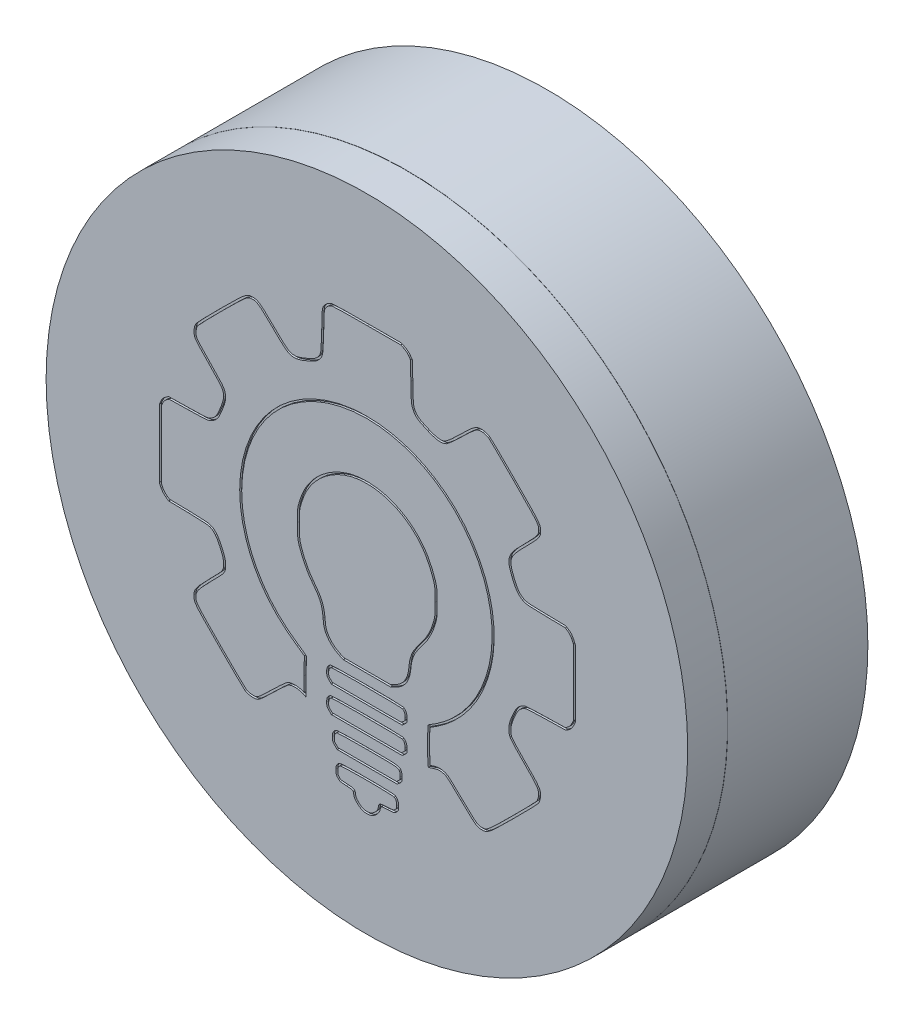
SolidWorks part; units mm, degrees
ref_plane "Front Plane" through (0, 0, 0) normal (0, 0, 1) x (1, 0, 0)
ref_plane "Top Plane" through (0, 0, 0) normal (0, 1, 0) x (1, 0, 0)
ref_plane "Right Plane" through (0, 0, 0) normal (1, 0, 0) x (0, 0, -1)
sketch "Sketch1" plane through (0, 0, 0) normal (0, 0, 1) x (1, 0, 0)
  circle A0 centre (0, 0) radius 15.025
  circle A1 centre (0, 0) radius 16.025
  dimension "D1" = 30.05
  dimension "D2" = 1
extrude "Boss-Extrude1" add sketch "Sketch1" along normal blind 7
sketch "Sketch2" plane through (0, 0, 7) normal (0, 0, 1) x (1, 0, 0)
  circle A0 centre (0, 0) radius 16.025
  circle A1 centre (0, 0) radius 16.025 construction
  point P8 (0, 0)
extrude "Boss-Extrude3" add sketch "Sketch2" along normal blind 2
sketch "Sketch4" plane through (0, 0, 9) normal (0, 0, 1) x (1, 0, 0)
  line L0 (-8.9288, 2.3101) -> (-9.9025, 2.2925)
  line L1 (-9.9025, 2.2925) -> (-10.0506, 2.1937)
  line L2 (-10.287, 1.9115) -> (-10.3717, 1.7281)
  line L3 (-10.3717, 1.7281) -> (-10.3717, 0.0312)
  line L4 (-10.3717, 0.0312) -> (-10.3717, -1.6621)
  line L5 (-10.3717, -1.6621) -> (-10.2835, -1.8421)
  line L6 (-10.0471, -2.1208) -> (-9.9025, -2.2231)
  line L7 (-9.9025, -2.2231) -> (-8.9288, -2.2407)
  line L8 (-3.1997, -7.2043) -> (-3.0339, -7.2819)
  line L9 (-3.0339, -7.2819) -> (-3.0339, -6.3999)
  line L10 (8.9641, -2.2442) -> (9.9378, -2.2231)
  line L11 (9.9378, -2.2231) -> (10.0789, -2.1278)
  line L12 (10.3152, -1.8491) -> (10.407, -1.6621)
  line L13 (10.407, -1.6621) -> (10.407, 0.0312)
  line L14 (10.407, 0.0312) -> (10.407, 1.7281)
  line L15 (10.407, 1.7281) -> (10.3223, 1.9115)
  line L16 (10.0859, 2.1937) -> (9.9378, 2.2925)
  line L17 (9.9378, 2.2925) -> (8.9641, 2.3101)
  line L18 (2.2931, 8.9988) -> (2.2754, 9.9548)
  line L19 (2.2754, 9.9548) -> (2.1802, 10.096)
  line L20 (1.9015, 10.3323) -> (1.7145, 10.424)
  line L21 (1.7145, 10.424) -> (0.0212, 10.4205)
  line L22 (-1.4182, -4.6149) -> (-1.1818, -4.7278)
  line L23 (-1.1818, -4.7278) -> (0, -4.7278)
  line L24 (0, -4.7278) -> (1.1818, -4.7278)
  line L25 (1.1818, -4.7278) -> (1.4182, -4.6149)
  line L26 (-1.8909, -5.966) -> (-1.7709, -6.086)
  line L27 (-1.7709, -6.086) -> (-0.0035, -6.086)
  line L28 (-0.0035, -6.086) -> (1.7604, -6.086)
  line L29 (1.7604, -6.086) -> (1.8874, -5.9766)
  line L30 (-1.8909, -7.2815) -> (-1.7709, -7.4014)
  line L31 (-1.7709, -7.4014) -> (-0.0035, -7.4014)
  line L32 (-0.0035, -7.4014) -> (1.7604, -7.4014)
  line L33 (1.7604, -7.4014) -> (1.8874, -7.292)
  line L34 (-1.6087, -8.6471) -> (-1.4887, -8.7671)
  line L35 (-1.4887, -8.7671) -> (0.0141, -8.7671)
  line L36 (0.0141, -8.7671) -> (1.5134, -8.7671)
  line L37 (1.5134, -8.7671) -> (1.6404, -8.6577)
  line L76 (-8.927, 2.2102) -> (-9.8714, 2.193)
  line L77 (-9.8714, 2.193) -> (-9.9945, 2.111)
  line L78 (-10.1966, 1.8688) -> (-10.2717, 1.7061)
  line L79 (-10.2717, 1.7061) -> (-10.2717, 0.0312)
  line L80 (-10.2717, 0.0312) -> (-10.2717, -1.6389)
  line L81 (-10.2717, -1.6389) -> (-10.194, -1.7973)
  line L82 (-9.9909, -2.0381) -> (-9.8699, -2.1236)
  line L83 (-9.8699, -2.1236) -> (-8.927, -2.1407)
  line L84 (-3.1583, -7.1133) -> (-3.1339, -7.1247)
  line L85 (-3.1339, -7.1247) -> (-3.1339, -6.3999)
  line L86 (8.9619, -2.1442) -> (9.9062, -2.1237)
  line L87 (9.9062, -2.1237) -> (10.0235, -2.0445)
  line L88 (10.2258, -1.8044) -> (10.307, -1.6389)
  line L89 (10.307, -1.6389) -> (10.307, 0.0312)
  line L90 (10.307, 0.0312) -> (10.307, 1.7061)
  line L91 (10.307, 1.7061) -> (10.2319, 1.8688)
  line L92 (10.0298, 2.111) -> (9.9067, 2.193)
  line L93 (9.9067, 2.193) -> (8.9622, 2.2102)
  line L94 (2.1931, 8.997) -> (2.176, 9.9234)
  line L95 (2.176, 9.9234) -> (2.0969, 10.0406)
  line L96 (1.8568, 10.2429) -> (1.6914, 10.324)
  line L97 (1.6914, 10.324) -> (0.0212, 10.3205)
  line L98 (-1.3752, -4.5246) -> (-1.1592, -4.6278)
  line L99 (-1.1592, -4.6278) -> (0, -4.6278)
  line L100 (0, -4.6278) -> (1.1592, -4.6278)
  line L101 (1.1592, -4.6278) -> (1.3753, -4.5245)
  line L102 (-1.8202, -5.8953) -> (-1.7295, -5.986)
  line L103 (-1.7295, -5.986) -> (-0.0035, -5.986)
  line L104 (-0.0035, -5.986) -> (1.7232, -5.986)
  line L105 (1.7232, -5.986) -> (1.8212, -5.9016)
  line L106 (-1.8202, -7.2108) -> (-1.7295, -7.3014)
  line L107 (-1.7295, -7.3014) -> (-0.0035, -7.3014)
  line L108 (-0.0035, -7.3014) -> (1.7232, -7.3014)
  line L109 (1.7232, -7.3014) -> (1.8212, -7.2171)
  line L110 (-1.538, -8.5764) -> (-1.4473, -8.6671)
  line L111 (-1.4473, -8.6671) -> (0.0141, -8.6671)
  line L112 (0.0141, -8.6671) -> (1.4763, -8.6671)
  line L113 (1.4763, -8.6671) -> (1.5743, -8.5827)
  spline S0 degree 3 poles (-1.7815, 10.3817) (-1.9438, 10.3217) (-2.0673, 10.223) (-2.159, 10.0783) knots 0 0 0 0 1 1 1 1
  spline S1 degree 3 poles (-2.159, 10.0783) (-2.2366, 9.9513) (-2.2401, 9.9125) (-2.2578, 8.9953) knots 0 0 0 0 1 1 1 1
  spline S2 degree 3 poles (-2.2578, 8.9953) (-2.2789, 7.944) (-2.2895, 7.8911) (-2.5118, 7.6688) knots 0 0 0 0 1 1 1 1
  spline S3 degree 3 poles (-2.5118, 7.6688) (-2.6564, 7.5207) (-3.2879, 7.249) (-3.5384, 7.2208) knots 0 0 0 0 1 1 1 1
  spline S4 degree 3 poles (-3.5384, 7.2208) (-3.8488, 7.1891) (-3.9582, 7.2631) (-4.6426, 7.944) knots 0 0 0 0 1 1 1 1
  spline S5 degree 3 poles (-4.6426, 7.944) (-5.2811, 8.579) (-5.4398, 8.6919) (-5.6797, 8.6954) knots 0 0 0 0 1 1 1 1
  spline S6 degree 3 poles (-5.6797, 8.6954) (-6.0043, 8.6954) (-6.0149, 8.6884) (-7.2778, 7.4325) knots 0 0 0 0 1 1 1 1
  spline S7 degree 3 poles (-7.2778, 7.4325) (-7.934, 6.7763) (-8.5019, 6.1942) (-8.5408, 6.1307) knots 0 0 0 0 1 1 1 1
  spline S8 degree 3 poles (-8.5408, 6.1307) (-8.6325, 5.9826) (-8.6642, 5.7074) (-8.6078, 5.5345) knots 0 0 0 0 1 1 1 1
  spline S9 degree 3 poles (-8.6078, 5.5345) (-8.5725, 5.4322) (-8.3926, 5.2241) (-7.8987, 4.7231) knots 0 0 0 0 1 1 1 1
  spline S10 degree 3 poles (-7.8987, 4.7231) (-7.1967, 4.0105) (-7.1614, 3.9576) (-7.1614, 3.626) knots 0 0 0 0 1 1 1 1
  spline S11 degree 3 poles (-7.1614, 3.626) (-7.1614, 3.4355) (-7.4189, 2.7829) (-7.5565, 2.61) knots 0 0 0 0 1 1 1 1
  spline S12 degree 3 poles (-7.5565, 2.61) (-7.6165, 2.543) (-7.7294, 2.4477) (-7.807, 2.4054) knots 0 0 0 0 1 1 1 1
  spline S13 degree 3 poles (-7.807, 2.4054) (-7.9481, 2.3348) (-8.0116, 2.3278) (-8.9288, 2.3101) knots 0 0 0 0 1 1 1 1
  spline S14 degree 3 poles (-10.0506, 2.1937) (-10.153, 2.1232) (-10.227, 2.0385) (-10.287, 1.9115) knots 0 0 0 0 1 1 1 1
  spline S15 degree 3 poles (-10.2835, -1.8421) (-10.227, -1.9549) (-10.1388, -2.0608) (-10.0471, -2.1208) knots 0 0 0 0 1 1 1 1
  spline S16 degree 3 poles (-8.9288, -2.2407) (-7.8281, -2.2619) (-7.7929, -2.2689) (-7.5706, -2.5264) knots 0 0 0 0 1 1 1 1
  spline S17 degree 3 poles (-7.5706, -2.5264) (-7.4295, -2.6923) (-7.2108, -3.172) (-7.1649, -3.4296) knots 0 0 0 0 1 1 1 1
  spline S18 degree 3 poles (-7.1649, -3.4296) (-7.1473, -3.5178) (-7.1508, -3.6518) (-7.1684, -3.7506) knots 0 0 0 0 1 1 1 1
  spline S19 degree 3 poles (-7.1684, -3.7506) (-7.2037, -3.9023) (-7.2566, -3.9693) (-7.8528, -4.569) knots 0 0 0 0 1 1 1 1
  spline S20 degree 3 poles (-7.8528, -4.569) (-8.5196, -5.2428) (-8.6395, -5.4122) (-8.6431, -5.6591) knots 0 0 0 0 1 1 1 1
  spline S21 degree 3 poles (-8.6431, -5.6591) (-8.6431, -5.9801) (-8.6289, -5.9978) (-7.3766, -7.2607) knots 0 0 0 0 1 1 1 1
  spline S22 degree 3 poles (-7.3766, -7.2607) (-6.7239, -7.9169) (-6.1419, -8.4849) (-6.0784, -8.5237) knots 0 0 0 0 1 1 1 1
  spline S23 degree 3 poles (-6.0784, -8.5237) (-5.9302, -8.6154) (-5.655, -8.6471) (-5.4822, -8.5907) knots 0 0 0 0 1 1 1 1
  spline S24 degree 3 poles (-5.4822, -8.5907) (-5.3799, -8.5589) (-5.1788, -8.3826) (-4.6919, -7.9028) knots 0 0 0 0 1 1 1 1
  spline S25 degree 3 poles (-4.6919, -7.9028) (-4.3321, -7.55) (-3.9829, -7.229) (-3.9158, -7.1937) knots 0 0 0 0 1 1 1 1
  spline S26 degree 3 poles (-3.9158, -7.1937) (-3.743, -7.102) (-3.4149, -7.109) (-3.1997, -7.2043) knots 0 0 0 0 1 1 1 1
  spline S27 degree 3 poles (-3.0339, -6.3999) (-3.0339, -5.9166) (-3.0304, -5.5109) (-3.0268, -5.4933) knots 0 0 0 0 1 1 1 1
  spline S28 degree 3 poles (-3.0268, -5.4933) (-3.0268, -5.4792) (-3.2068, -5.3451) (-3.4325, -5.1934) knots 0 0 0 0 1 1 1 1
  spline S29 degree 3 poles (-3.4325, -5.1934) (-4.6567, -4.375) (-5.4892, -3.2884) (-5.9408, -1.9197) knots 0 0 0 0 1 1 1 1
  spline S30 degree 3 poles (-5.9408, -1.9197) (-6.7804, 0.6098) (-5.8984, 3.432) (-3.7712, 5.0336) knots 0 0 0 0 1 1 1 1
  spline S31 degree 3 poles (-3.7712, 5.0336) (-1.6898, 6.5964) (1.1183, 6.7163) (3.3338, 5.3334) knots 0 0 0 0 1 1 1 1
  spline S32 degree 3 poles (3.3338, 5.3334) (5.7503, 3.8271) (6.8404, 0.8108) (5.9443, -1.9056) knots 0 0 0 0 1 1 1 1
  spline S33 degree 3 poles (5.9443, -1.9056) (5.5033, -3.2532) (4.6496, -4.3785) (3.4713, -5.1688) knots 0 0 0 0 1 1 1 1
  spline S34 degree 3 poles (3.4713, -5.1688) (3.2738, -5.2993) (3.0974, -5.4122) (3.0727, -5.4192) knots 0 0 0 0 1 1 1 1
  spline S35 degree 3 poles (3.0727, -5.4192) (3.0092, -5.4404) (3.0127, -7.2713) (3.0762, -7.2607) knots 0 0 0 0 1 1 1 1
  spline S36 degree 3 poles (3.0762, -7.2607) (3.1009, -7.2572) (3.2173, -7.2184) (3.3338, -7.1796) knots 0 0 0 0 1 1 1 1
  spline S37 degree 3 poles (3.3338, -7.1796) (3.5631, -7.0949) (3.7712, -7.1055) (3.9688, -7.2043) knots 0 0 0 0 1 1 1 1
  spline S38 degree 3 poles (3.9688, -7.2043) (4.0252, -7.236) (4.3603, -7.5429) (4.7096, -7.8887) knots 0 0 0 0 1 1 1 1
  spline S39 degree 3 poles (4.7096, -7.8887) (5.3516, -8.5237) (5.4928, -8.626) (5.7185, -8.626) knots 0 0 0 0 1 1 1 1
  spline S40 degree 3 poles (5.7185, -8.626) (6.0325, -8.626) (6.0572, -8.6083) (7.3131, -7.3595) knots 0 0 0 0 1 1 1 1
  spline S41 degree 3 poles (7.3131, -7.3595) (7.9693, -6.7069) (8.5372, -6.1248) (8.576, -6.0613) knots 0 0 0 0 1 1 1 1
  spline S42 degree 3 poles (8.576, -6.0613) (8.6148, -6.0013) (8.6536, -5.8708) (8.6678, -5.772) knots 0 0 0 0 1 1 1 1
  spline S43 degree 3 poles (8.6678, -5.772) (8.7066, -5.4439) (8.636, -5.3381) (7.9269, -4.6255) knots 0 0 0 0 1 1 1 1
  spline S44 degree 3 poles (7.9269, -4.6255) (7.553, -4.2515) (7.2708, -3.9376) (7.239, -3.867) knots 0 0 0 0 1 1 1 1
  spline S45 degree 3 poles (7.239, -3.867) (7.1473, -3.6483) (7.172, -3.4225) (7.3201, -3.0521) knots 0 0 0 0 1 1 1 1
  spline S46 degree 3 poles (7.3201, -3.0521) (7.5177, -2.5653) (7.6235, -2.4277) (7.9022, -2.3042) knots 0 0 0 0 1 1 1 1
  spline S47 degree 3 poles (7.9022, -2.3042) (7.9551, -2.2795) (8.3644, -2.2548) (8.9641, -2.2442) knots 0 0 0 0 1 1 1 1
  spline S48 degree 3 poles (10.0789, -2.1278) (10.1706, -2.0678) (10.2553, -1.9691) (10.3152, -1.8491) knots 0 0 0 0 1 1 1 1
  spline S49 degree 3 poles (10.3223, 1.9115) (10.2623, 2.0385) (10.1882, 2.1232) (10.0859, 2.1937) knots 0 0 0 0 1 1 1 1
  spline S50 degree 3 poles (8.9641, 2.3101) (8.0469, 2.3278) (7.9834, 2.3348) (7.8423, 2.4054) knots 0 0 0 0 1 1 1 1
  spline S51 degree 3 poles (7.8423, 2.4054) (7.6306, 2.5183) (7.5071, 2.6911) (7.3413, 3.1039) knots 0 0 0 0 1 1 1 1
  spline S52 degree 3 poles (7.3413, 3.1039) (7.0697, 3.7883) (7.1155, 3.9153) (7.9551, 4.7443) knots 0 0 0 0 1 1 1 1
  spline S53 degree 3 poles (7.9551, 4.7443) (8.5584, 5.3405) (8.6748, 5.4993) (8.6783, 5.7286) knots 0 0 0 0 1 1 1 1
  spline S54 degree 3 poles (8.6783, 5.7286) (8.6783, 6.0496) (8.6642, 6.0672) (7.4119, 7.3302) knots 0 0 0 0 1 1 1 1
  spline S55 degree 3 poles (7.4119, 7.3302) (6.7592, 7.9863) (6.1771, 8.5543) (6.1136, 8.5931) knots 0 0 0 0 1 1 1 1
  spline S56 degree 3 poles (6.1136, 8.5931) (6.0537, 8.6319) (5.9231, 8.6707) (5.8244, 8.6848) knots 0 0 0 0 1 1 1 1
  spline S57 degree 3 poles (5.8244, 8.6848) (5.4963, 8.7236) (5.3834, 8.6531) (4.6743, 7.9511) knots 0 0 0 0 1 1 1 1
  spline S58 degree 3 poles (4.6743, 7.9511) (4.2863, 7.5701) (3.9864, 7.302) (3.9053, 7.2667) knots 0 0 0 0 1 1 1 1
  spline S59 degree 3 poles (3.9053, 7.2667) (3.6901, 7.1785) (3.5101, 7.1996) (3.0903, 7.3725) knots 0 0 0 0 1 1 1 1
  spline S60 degree 3 poles (3.0903, 7.3725) (2.6282, 7.563) (2.5012, 7.6512) (2.3954, 7.8735) knots 0 0 0 0 1 1 1 1
  spline S61 degree 3 poles (2.3954, 7.8735) (2.3142, 8.0357) (2.3107, 8.0851) (2.2931, 8.9988) knots 0 0 0 0 1 1 1 1
  spline S62 degree 3 poles (2.1802, 10.096) (2.1202, 10.1877) (2.0214, 10.2723) (1.9015, 10.3323) knots 0 0 0 0 1 1 1 1
  spline S63 degree 3 poles (0.0212, 10.4205) (-1.083, 10.4205) (-1.7145, 10.4064) (-1.7815, 10.3817) knots 0 0 0 0 1 1 1 1
  spline S64 degree 3 poles (-0.5115, 3.5413) (-1.4499, 3.4073) (-2.3707, 2.8181) (-2.9139, 2.0068) knots 0 0 0 0 1 1 1 1
  spline S65 degree 3 poles (-2.9139, 2.0068) (-3.1327, 1.6751) (-3.2456, 1.4353) (-3.3761, 1.0084) knots 0 0 0 0 1 1 1 1
  spline S66 degree 3 poles (-3.3761, 1.0084) (-3.4643, 0.7262) (-3.4713, 0.6591) (-3.4713, 0.0524) knots 0 0 0 0 1 1 1 1
  spline S67 degree 3 poles (-3.4713, 0.0524) (-3.4713, -0.5615) (-3.4643, -0.6214) (-3.3761, -0.9142) knots 0 0 0 0 1 1 1 1
  spline S68 degree 3 poles (-3.3761, -0.9142) (-3.2526, -1.3129) (-2.981, -1.8421) (-2.7587, -2.1172) knots 0 0 0 0 1 1 1 1
  spline S69 degree 3 poles (-2.7587, -2.1172) (-2.3424, -2.6393) (-2.2366, -2.8792) (-2.1908, -3.4296) knots 0 0 0 0 1 1 1 1
  spline S70 degree 3 poles (-2.1908, -3.4296) (-2.1696, -3.7083) (-2.1414, -3.8317) (-2.0673, -3.9834) knots 0 0 0 0 1 1 1 1
  spline S71 degree 3 poles (-2.0673, -3.9834) (-1.9332, -4.2551) (-1.7004, -4.4808) (-1.4182, -4.6149) knots 0 0 0 0 1 1 1 1
  spline S72 degree 3 poles (1.4182, -4.6149) (1.8979, -4.3891) (2.1414, -4.0187) (2.1943, -3.4331) knots 0 0 0 0 1 1 1 1
  spline S73 degree 3 poles (2.1943, -3.4331) (2.2437, -2.8969) (2.3495, -2.6676) (2.8399, -2.0467) knots 0 0 0 0 1 1 1 1
  spline S74 degree 3 poles (2.8399, -2.0467) (3.0727, -1.7503) (3.2773, -1.3482) (3.4078, -0.9178) knots 0 0 0 0 1 1 1 1
  spline S75 degree 3 poles (3.4078, -0.9178) (3.4996, -0.6179) (3.5066, -0.5615) (3.5066, 0.0524) knots 0 0 0 0 1 1 1 1
  spline S76 degree 3 poles (3.5066, 0.0524) (3.5066, 0.6627) (3.4996, 0.7262) (3.4114, 1.0154) knots 0 0 0 0 1 1 1 1
  spline S77 degree 3 poles (3.4114, 1.0154) (3.2949, 1.3929) (3.0621, 1.8656) (2.8469, 2.1549) knots 0 0 0 0 1 1 1 1
  spline S78 degree 3 poles (2.8469, 2.1549) (2.0849, 3.1886) (0.7832, 3.7248) (-0.5115, 3.5413) knots 0 0 0 0 1 1 1 1
  spline S79 degree 3 poles (-1.8168, -5.2816) (-1.9544, -5.3557) (-2.0108, -5.4616) (-2.0108, -5.6556) knots 0 0 0 0 1 1 1 1
  spline S80 degree 3 poles (-2.0108, -5.6556) (-2.0108, -5.8249) (-1.9967, -5.8602) (-1.8909, -5.966) knots 0 0 0 0 1 1 1 1
  spline S81 degree 3 poles (1.8874, -5.9766) (1.9967, -5.8778) (2.0108, -5.8496) (2.0108, -5.6909) knots 0 0 0 0 1 1 1 1
  spline S82 degree 3 poles (2.0108, -5.6909) (2.0108, -5.4827) (1.9438, -5.3381) (1.8168, -5.2816) knots 0 0 0 0 1 1 1 1
  spline S83 degree 3 poles (1.8168, -5.2816) (1.6933, -5.2252) (-1.7145, -5.2217) (-1.8168, -5.2816) knots 0 0 0 0 1 1 1 1
  spline S84 degree 3 poles (-1.8168, -6.5971) (-1.9544, -6.6712) (-2.0108, -6.777) (-2.0108, -6.971) knots 0 0 0 0 1 1 1 1
  spline S85 degree 3 poles (-2.0108, -6.971) (-2.0108, -7.1404) (-1.9967, -7.1756) (-1.8909, -7.2815) knots 0 0 0 0 1 1 1 1
  spline S86 degree 3 poles (1.8874, -7.292) (1.9967, -7.1933) (2.0108, -7.165) (2.0108, -7.0063) knots 0 0 0 0 1 1 1 1
  spline S87 degree 3 poles (2.0108, -7.0063) (2.0108, -6.8052) (1.9332, -6.65) (1.8098, -6.5935) knots 0 0 0 0 1 1 1 1
  spline S88 degree 3 poles (1.8098, -6.5935) (1.6898, -6.5406) (-1.718, -6.5406) (-1.8168, -6.5971) knots 0 0 0 0 1 1 1 1
  spline S89 degree 3 poles (-1.5346, -7.9628) (-1.6722, -8.0368) (-1.7286, -8.1427) (-1.7286, -8.3367) knots 0 0 0 0 1 1 1 1
  spline S90 degree 3 poles (-1.7286, -8.3367) (-1.7286, -8.506) (-1.7145, -8.5413) (-1.6087, -8.6471) knots 0 0 0 0 1 1 1 1
  spline S91 degree 3 poles (1.6404, -8.6577) (1.7498, -8.5589) (1.7639, -8.5272) (1.7639, -8.3755) knots 0 0 0 0 1 1 1 1
  spline S92 degree 3 poles (1.7639, -8.3755) (1.7639, -8.2838) (1.7463, -8.1638) (1.7216, -8.1144) knots 0 0 0 0 1 1 1 1
  spline S93 degree 3 poles (1.7216, -8.1144) (1.6334, -7.9239) (1.6087, -7.9204) (0.0106, -7.9204) knots 0 0 0 0 1 1 1 1
  spline S94 degree 3 poles (0.0106, -7.9204) (-0.9948, -7.9239) (-1.4852, -7.9345) (-1.5346, -7.9628) knots 0 0 0 0 1 1 1 1
  spline S95 degree 3 poles (-1.3688, -9.3068) (-1.4923, -9.3774) (-1.5522, -9.4868) (-1.5558, -9.6561) knots 0 0 0 0 1 1 1 1
  spline S96 degree 3 poles (-1.5558, -9.6561) (-1.5628, -9.8254) (-1.5275, -9.9136) (-1.4111, -10.0194) knots 0 0 0 0 1 1 1 1
  spline S97 degree 3 poles (-1.4111, -10.0194) (-1.3511, -10.0759) (-1.2665, -10.0935) (-1.0125, -10.1076) knots 0 0 0 0 1 1 1 1
  spline S98 degree 3 poles (-1.0125, -10.1076) (-0.7232, -10.1218) (-0.6879, -10.1323) (-0.6773, -10.1958) knots 0 0 0 0 1 1 1 1
  spline S99 degree 3 poles (-0.6773, -10.1958) (-0.6526, -10.3758) (-0.6279, -10.4322) (-0.5186, -10.5521) knots 0 0 0 0 1 1 1 1
  spline S100 degree 3 poles (-0.5186, -10.5521) (-0.2258, -10.8908) (0.2258, -10.8908) (0.5186, -10.5521) knots 0 0 0 0 1 1 1 1
  spline S101 degree 3 poles (0.5186, -10.5521) (0.6279, -10.4322) (0.6526, -10.3758) (0.6773, -10.1958) knots 0 0 0 0 1 1 1 1
  spline S102 degree 3 poles (0.6773, -10.1958) (0.6879, -10.1323) (0.7232, -10.1253) (1.0301, -10.1076) knots 0 0 0 0 1 1 1 1
  spline S103 degree 3 poles (1.0301, -10.1076) (1.3476, -10.09) (1.3794, -10.0829) (1.4781, -9.9877) knots 0 0 0 0 1 1 1 1
  spline S104 degree 3 poles (1.4781, -9.9877) (1.5699, -9.8995) (1.5875, -9.8572) (1.5875, -9.7161) knots 0 0 0 0 1 1 1 1
  spline S105 degree 3 poles (1.5875, -9.7161) (1.5875, -9.5044) (1.5311, -9.3739) (1.4076, -9.3104) knots 0 0 0 0 1 1 1 1
  spline S106 degree 3 poles (1.4076, -9.3104) (1.2735, -9.2433) (-1.2453, -9.2398) (-1.3688, -9.3068) knots 0 0 0 0 1 1 1 1
  spline S171 degree 3 poles (-9.9945, 2.111) (-10.016, 2.0961) (-10.0581, 2.0634) (-10.1096, 2.0103) (-10.155, 1.9489) (-10.1841, 1.8952) (-10.1966, 1.8688) knots 0.002323 0.002323 0.002323 0.002323 0.251742 0.501161 0.750581 1 1 1 1
  spline S172 degree 3 poles (-10.194, -1.7973) (-10.1815, -1.8224) (-10.1533, -1.8709) (-10.1025, -1.939) (-10.0459, -1.9976) (-10.0105, -2.0252) (-9.9909, -2.0381) knots 0 0 0 0 0.25139 0.502779 0.754169 1.005559 1.005559 1.005559 1.005559
  spline S173 degree 3 poles (-8.927, -2.1407) (-8.8622, -2.142) (-8.7269, -2.1446) (-8.5014, -2.1497) (-8.267, -2.1573) (-8.0555, -2.1716) (-7.8404, -2.202) (-7.652, -2.2805) (-7.5463, -2.4016) (-7.4947, -2.4614) knots -0.000034 -0.000034 -0.000034 -0.000034 0.062489 0.125013 0.250059 0.375105 0.500152 0.750245 1.000338 1.000338 1.000338 1.000338
  spline S174 degree 3 poles (-7.4947, -2.4614) (-7.4718, -2.4883) (-7.4326, -2.5422) (-7.3457, -2.6846) (-7.2387, -2.8972) (-7.1262, -3.1786) (-7.0814, -3.3287) (-7.0667, -3.411) knots -0.000527 -0.000527 -0.000527 -0.000527 0.124393 0.249313 0.499154 0.748994 0.998835 0.998835 0.998835 0.998835
  spline S175 degree 3 poles (-7.0667, -3.411) (-7.061, -3.4396) (-7.0544, -3.4962) (-7.0523, -3.5896) (-7.0576, -3.6843) (-7.0653, -3.7416) (-7.0705, -3.7707) knots 0.003226 0.003226 0.003226 0.003226 0.25457 0.505915 0.757259 1.008604 1.008604 1.008604 1.008604
  spline S176 degree 3 poles (-7.0705, -3.7707) (-7.081, -3.8159) (-7.1061, -3.8986) (-7.1896, -4.0189) (-7.3029, -4.1477) (-7.4192, -4.2712) (-7.5487, -4.404) (-7.6727, -4.5295) (-7.7464, -4.6038) (-7.7818, -4.6394) knots -0.005543 -0.005543 -0.005543 -0.005543 0.245831 0.497206 0.622893 0.74858 0.874267 0.937111 0.999954 0.999954 0.999954 0.999954
  spline S177 degree 3 poles (-7.7818, -4.6394) (-7.8213, -4.6794) (-7.903, -4.7623) (-8.0426, -4.9059) (-8.1904, -5.0622) (-8.3243, -5.2136) (-8.4531, -5.3775) (-8.53, -5.518) (-8.5423, -5.6102) (-8.5431, -5.6599) knots 0.000041 0.000041 0.000041 0.000041 0.062471 0.124902 0.249763 0.374624 0.499485 0.749207 0.998929 0.998929 0.998929 0.998929
  spline S178 degree 3 poles (-8.5431, -5.6599) (-8.5431, -5.6934) (-8.5422, -5.7678) (-8.5296, -5.835) (-8.4939, -5.9176) (-8.4111, -6.0367) (-8.2656, -6.2062) (-8.0455, -6.4398) (-7.7864, -6.7046) (-7.5327, -6.9612) (-7.3791, -7.1162) (-7.3056, -7.1903) knots 0.000773 0.000773 0.000773 0.000773 0.125675 0.250576 0.375478 0.50038 0.625281 0.750183 0.875084 0.937535 0.999986 0.999986 0.999986 0.999986
  spline S179 degree 3 poles (-7.3056, -7.1903) (-7.1534, -7.3434) (-6.8333, -7.663) (-6.5033, -7.9879) (-6.288, -8.1965) (-6.1575, -8.3208) (-6.0804, -8.3921) (-6.037, -8.4297) (-6.0305, -8.4351) (-6.0251, -8.4391) knots 0.000027 0.000027 0.000027 0.000027 0.244111 0.488195 0.610236 0.732278 0.85432 0.915341 0.976362 0.976362 0.976362 0.976362
  spline S180 degree 3 poles (-6.0251, -8.4391) (-5.9917, -8.4596) (-5.9247, -8.487) (-5.778, -8.5183) (-5.6271, -8.5206) (-5.5514, -8.5081) (-5.5125, -8.4954) knots 0.002003 0.002003 0.002003 0.002003 0.251839 0.501675 0.751511 1.001347 1.001347 1.001347 1.001347
  spline S181 degree 3 poles (-5.5125, -8.4954) (-5.5036, -8.4927) (-5.492, -8.4876) (-5.4286, -8.4493) (-5.3113, -8.3552) (-5.1265, -8.1855) (-4.9377, -8.0039) (-4.8183, -7.8869) (-4.762, -7.8315) knots -0.002287 -0.002287 -0.002287 -0.002287 0.123007 0.248301 0.498888 0.749476 0.87477 1.000063 1.000063 1.000063 1.000063
  spline S182 degree 3 poles (-4.762, -7.8315) (-4.6745, -7.7456) (-4.4913, -7.5687) (-4.2531, -7.3461) (-4.0982, -7.2079) (-4.0116, -7.1375) (-3.9812, -7.1151) (-3.9626, -7.1053) knots -0.000086 -0.000086 -0.000086 -0.000086 0.249847 0.499779 0.749712 0.874679 0.999645 0.999645 0.999645 0.999645
  spline S183 degree 3 poles (-3.9626, -7.1053) (-3.9056, -7.0751) (-3.7837, -7.0383) (-3.5723, -7.0224) (-3.3545, -7.0457) (-3.2219, -7.0851) (-3.1583, -7.1133) knots 0.000189 0.000189 0.000189 0.000189 0.250515 0.500841 0.751167 1.001494 1.001494 1.001494 1.001494
  spline S184 degree 3 poles (-3.1339, -6.3999) (-3.1339, -6.3042) (-3.1336, -6.1049) (-3.1324, -5.8534) (-3.131, -5.6865) (-3.1297, -5.5845) (-3.1291, -5.5521) (-3.1286, -5.5336) knots 0 0 0 0 0.206567 0.413133 0.6197 0.722983 0.826266 0.826266 0.826266 0.826266
  spline S185 degree 3 poles (-3.1286, -5.5336) (-3.1478, -5.518) (-3.181, -5.4925) (-3.268, -5.4286) (-3.3692, -5.3574) (-3.4494, -5.3026) (-3.4882, -5.2765) knots 0.27751 0.27751 0.27751 0.27751 0.458097 0.638685 0.819273 0.99986 0.99986 0.99986 0.99986
  spline S186 degree 3 poles (-3.4882, -5.2765) (-3.7904, -5.0745) (-4.3735, -4.6177) (-5.0796, -3.841) (-5.6427, -2.9607) (-5.9237, -2.2908) (-6.0357, -1.9511) knots 0.000025 0.000025 0.000025 0.000025 0.250014 0.500002 0.749991 0.999979 0.999979 0.999979 0.999979
  spline S187 degree 3 poles (-6.0357, -1.9511) (-6.1411, -1.6336) (-6.3016, -0.9762) (-6.4067, 0.338) (-6.1586, 1.9643) (-5.4375, 3.4427) (-4.6038, 4.4633) (-4.0984, 4.9124) (-3.8313, 5.1135) knots 0.000011 0.000011 0.000011 0.000011 0.125011 0.250011 0.50001 0.750009 0.875009 1.000008 1.000008 1.000008 1.000008
  spline S188 degree 3 poles (-3.8313, 5.1135) (-3.5705, 5.3094) (-3.0139, 5.6642) (-1.8414, 6.1804) (-0.2775, 6.482) (1.3077, 6.3138) (2.5224, 5.8984) (3.1092, 5.5915) (3.3867, 5.4183) knots -0.000008 -0.000008 -0.000008 -0.000008 0.124992 0.249993 0.499994 0.749995 0.874996 0.999996 0.999996 0.999996 0.999996
  spline S189 degree 3 poles (3.3867, 5.4183) (3.6895, 5.2295) (4.2674, 4.7951) (5.2291, 3.7725) (6.081, 2.2403) (6.4045, 0.5152) (6.3184, -0.89) (6.1515, -1.5965) (6.0393, -1.9368) knots 0.000004 0.000004 0.000004 0.000004 0.125001 0.249999 0.499995 0.749991 0.874988 0.999986 0.999986 0.999986 0.999986
  spline S190 degree 3 poles (6.0393, -1.9368) (5.9288, -2.2744) (5.6505, -2.9371) (5.087, -3.8242) (4.3848, -4.6066) (3.8219, -5.054) (3.5267, -5.252) knots 0.000028 0.000028 0.000028 0.000028 0.250041 0.500054 0.750068 1.000081 1.000081 1.000081 1.000081
  spline S191 degree 3 poles (3.5267, -5.252) (3.4884, -5.2773) (3.4089, -5.3296) (3.3051, -5.3968) (3.2142, -5.4541) (3.1768, -5.4769) (3.1548, -5.4895) knots -0.000485 -0.000485 -0.000485 -0.000485 0.199236 0.398958 0.598679 0.7984 0.7984 0.7984 0.7984
  spline S192 degree 3 poles (3.1548, -5.4895) (3.1522, -5.5068) (3.1489, -5.5366) (3.1412, -5.6343) (3.134, -5.79) (3.1285, -6.0198) (3.1263, -6.2717) (3.1274, -6.5285) (3.1318, -6.7724) (3.138, -6.9483) (3.1448, -7.0669) (3.1482, -7.111) (3.1504, -7.1348) knots 0.098872 0.098872 0.098872 0.098872 0.1454 0.191929 0.284986 0.378043 0.4711 0.564157 0.657214 0.750271 0.796799 0.843328 0.843328 0.843328 0.843328
  spline S193 degree 3 poles (3.1504, -7.1348) (3.1619, -7.1311) (3.1841, -7.1239) (3.2217, -7.1115) (3.2606, -7.0986) (3.2874, -7.0896) (3.3006, -7.0852) knots 0.536874 0.536874 0.536874 0.536874 0.651594 0.766314 0.881035 0.995755 0.995755 0.995755 0.995755
  spline S194 degree 3 poles (3.3006, -7.0852) (3.361, -7.063) (3.4885, -7.0281) (3.6701, -7.0169) (3.8475, -7.0442) (3.9616, -7.0889) (4.0157, -7.1159) knots 0.002041 0.002041 0.002041 0.002041 0.25245 0.50286 0.753269 1.003679 1.003679 1.003679 1.003679
  spline S195 degree 3 poles (4.0157, -7.1159) (4.0314, -7.1248) (4.0566, -7.1432) (4.136, -7.2089) (4.2829, -7.3408) (4.5139, -7.5574) (4.6942, -7.7327) (4.7799, -7.8176) knots -0.012546 -0.012546 -0.012546 -0.012546 0.11402 0.240587 0.493719 0.746852 0.999985 0.999985 0.999985 0.999985
  spline S196 degree 3 poles (4.7799, -7.8176) (4.818, -7.8552) (4.897, -7.9331) (5.0331, -8.0657) (5.1802, -8.2053) (5.3208, -8.3308) (5.471, -8.4499) (5.5935, -8.517) (5.675, -8.526) (5.7185, -8.526) knots 0.000008 0.000008 0.000008 0.000008 0.062508 0.125007 0.250006 0.375005 0.500004 0.750002 1 1 1 1
  spline S197 degree 3 poles (5.7185, -8.526) (5.7513, -8.526) (5.824, -8.525) (5.8903, -8.5124) (5.9729, -8.4763) (6.0921, -8.3931) (6.2616, -8.2474) (6.4949, -8.0274) (6.759, -7.7685) (7.0146, -7.5152) (7.1688, -7.3619) (7.2426, -7.2886) knots 0 0 0 0 0.125 0.25 0.375 0.499999 0.624999 0.749999 0.874999 0.937499 0.999999 0.999999 0.999999 0.999999
  spline S198 degree 3 poles (7.2426, -7.2886) (7.3956, -7.1364) (7.7151, -6.8166) (8.0398, -6.4867) (8.2484, -6.2714) (8.3727, -6.1408) (8.4442, -6.0636) (8.4818, -6.0202) (8.4874, -6.0136) (8.4914, -6.008) knots 0.000002 0.000002 0.000002 0.000002 0.243936 0.48787 0.609837 0.731803 0.85377 0.914754 0.975737 0.975737 0.975737 0.975737
  spline S199 degree 3 poles (8.4914, -6.008) (8.4997, -5.9952) (8.5104, -5.9733) (8.5361, -5.9041) (8.5563, -5.8282) (8.5652, -5.7827) (8.5686, -5.759) knots -0.00601 -0.00601 -0.00601 -0.00601 0.244357 0.494724 0.745091 0.995458 0.995458 0.995458 0.995458
  spline S200 degree 3 poles (8.5686, -5.759) (8.5726, -5.7248) (8.5788, -5.6502) (8.5702, -5.546) (8.5289, -5.4406) (8.4125, -5.2827) (8.2816, -5.1331) (8.1305, -4.9743) (7.9847, -4.8256) (7.8979, -4.7381) (7.8561, -4.6961) knots 0.001315 0.001315 0.001315 0.001315 0.126145 0.250976 0.500637 0.625467 0.750298 0.875128 0.937544 0.999959 0.999959 0.999959 0.999959
  spline S201 degree 3 poles (7.8561, -4.6961) (7.7673, -4.6073) (7.5815, -4.4172) (7.3688, -4.1897) (7.2137, -4.0074) (7.1667, -3.9499) (7.1473, -3.9069) knots 0.000078 0.000078 0.000078 0.000078 0.251447 0.502815 0.754184 1.005552 1.005552 1.005552 1.005552
  spline S202 degree 3 poles (7.1473, -3.9069) (7.1216, -3.8455) (7.0843, -3.7174) (7.0824, -3.5092) (7.1265, -3.2877) (7.1929, -3.101) (7.2274, -3.0147) knots -0.001811 -0.001811 -0.001811 -0.001811 0.248694 0.499199 0.749703 1.000208 1.000208 1.000208 1.000208
  spline S203 degree 3 poles (7.2274, -3.0147) (7.2505, -2.9579) (7.3005, -2.8385) (7.3875, -2.6527) (7.4974, -2.4698) (7.654, -2.3168) (7.7917, -2.2438) (7.8611, -2.213) knots -0.000158 -0.000158 -0.000158 -0.000158 0.124775 0.249708 0.499574 0.74944 0.999307 0.999307 0.999307 0.999307
  spline S204 degree 3 poles (7.8611, -2.213) (7.9029, -2.194) (7.9763, -2.1884) (8.2068, -2.1679) (8.4813, -2.1565) (8.7413, -2.1487) (8.8899, -2.1455) (8.9619, -2.1442) knots 0.001885 0.001885 0.001885 0.001885 0.251357 0.500829 0.750301 0.875037 0.999773 0.999773 0.999773 0.999773
  spline S205 degree 3 poles (10.0235, -2.0445) (10.043, -2.0318) (10.0786, -2.0043) (10.1334, -1.9481) (10.1831, -1.8818) (10.2128, -1.8304) (10.2258, -1.8044) knots -0.002232 -0.002232 -0.002232 -0.002232 0.248326 0.498884 0.749442 1 1 1 1
  spline S206 degree 3 poles (10.2319, 1.8688) (10.2194, 1.8952) (10.1903, 1.9489) (10.1449, 2.0103) (10.0934, 2.0634) (10.0513, 2.0961) (10.0298, 2.111) knots 0 0 0 0 0.249419 0.498839 0.748258 0.997677 0.997677 0.997677 0.997677
  spline S207 degree 3 poles (8.9622, 2.2102) (8.9079, 2.2112) (8.7948, 2.2134) (8.6054, 2.2175) (8.4076, 2.2225) (8.2294, 2.2293) (8.0528, 2.2407) (7.9111, 2.2632) (7.8363, 2.2966) (7.7964, 2.3165) knots 0 0 0 0 0.062674 0.125347 0.250695 0.376042 0.50139 0.752085 1.00278 1.00278 1.00278 1.00278
  spline S208 degree 3 poles (7.7964, 2.3165) (7.7381, 2.3476) (7.6283, 2.421) (7.491, 2.5745) (7.3902, 2.7467) (7.3112, 2.9148) (7.2683, 3.0174) (7.2484, 3.0668) knots -0.001828 -0.001828 -0.001828 -0.001828 0.248668 0.499164 0.749659 0.874907 1.000155 1.000155 1.000155 1.000155
  spline S209 degree 3 poles (7.2484, 3.0668) (7.2171, 3.1457) (7.1533, 3.314) (7.0993, 3.5161) (7.0857, 3.7134) (7.1284, 3.9053) (7.2274, 4.0939) (7.3804, 4.2937) (7.5587, 4.4874) (7.7318, 4.6637) (7.835, 4.7663) (7.8849, 4.8155) knots -0.000094 -0.000094 -0.000094 -0.000094 0.124917 0.249928 0.374939 0.49995 0.624961 0.749972 0.874983 0.937488 0.999994 0.999994 0.999994 0.999994
  spline S210 degree 3 poles (7.8849, 4.8155) (7.9529, 4.8827) (8.0981, 5.0275) (8.2543, 5.1896) (8.3777, 5.3263) (8.4951, 5.4732) (8.5659, 5.6005) (8.5776, 5.6842) (8.5783, 5.7294) knots 0.000009 0.000009 0.000009 0.000009 0.12485 0.249692 0.374533 0.499375 0.749057 0.99874 0.99874 0.99874 0.99874
  spline S211 degree 3 poles (8.5783, 5.7294) (8.5783, 5.7629) (8.5775, 5.8372) (8.5649, 5.9045) (8.5292, 5.9871) (8.4464, 6.1062) (8.3008, 6.2757) (8.0808, 6.5093) (7.8217, 6.7741) (7.568, 7.0307) (7.4144, 7.1856) (7.3409, 7.2597) knots 0.000837 0.000837 0.000837 0.000837 0.12573 0.250624 0.375518 0.500411 0.625305 0.750199 0.875092 0.937539 0.999986 0.999986 0.999986 0.999986
  spline S212 degree 3 poles (7.3409, 7.2597) (7.1887, 7.4127) (6.8689, 7.7322) (6.539, 8.0569) (6.3237, 8.2655) (6.1932, 8.3898) (6.116, 8.4612) (6.0725, 8.4989) (6.0659, 8.5045) (6.0604, 8.5085) knots 0.000027 0.000027 0.000027 0.000027 0.243955 0.487882 0.609846 0.73181 0.853773 0.914755 0.975737 0.975737 0.975737 0.975737
  spline S213 degree 3 poles (6.0604, 8.5085) (6.0476, 8.5167) (6.0256, 8.5275) (5.9565, 8.5532) (5.8805, 8.5734) (5.835, 8.5823) (5.8114, 8.5857) knots -0.00601 -0.00601 -0.00601 -0.00601 0.244357 0.494724 0.74509 0.995457 0.995457 0.995457 0.995457
  spline S214 degree 3 poles (5.8114, 8.5857) (5.777, 8.5897) (5.7024, 8.5959) (5.5966, 8.5873) (5.4894, 8.5461) (5.3305, 8.4307) (5.1804, 8.3011) (5.0217, 8.1515) (4.8734, 8.0072) (4.7863, 7.9212) (4.7445, 7.8799) knots 0.001315 0.001315 0.001315 0.001315 0.12616 0.251004 0.500693 0.625537 0.750381 0.875225 0.937648 1.00007 1.00007 1.00007 1.00007
  spline S215 degree 3 poles (4.7445, 7.8799) (4.6537, 7.7907) (4.4585, 7.6026) (4.2322, 7.3937) (4.0506, 7.2418) (3.9887, 7.1939) (3.9442, 7.1745) knots -0.000128 -0.000128 -0.000128 -0.000128 0.250901 0.50193 0.752959 1.003988 1.003988 1.003988 1.003988
  spline S216 degree 3 poles (3.9442, 7.1745) (3.8855, 7.1505) (3.7634, 7.1137) (3.5672, 7.1134) (3.3802, 7.1582) (3.207, 7.218) (3.102, 7.2596) (3.0522, 7.28) knots -0.001517 -0.001517 -0.001517 -0.001517 0.248866 0.499248 0.749631 0.874823 1.000014 1.000014 1.000014 1.000014
  spline S217 degree 3 poles (3.0522, 7.28) (2.9986, 7.3022) (2.8856, 7.3498) (2.7111, 7.4304) (2.5412, 7.5267) (2.3985, 7.6591) (2.3332, 7.7716) (2.3055, 7.8296) knots -0.000013 -0.000013 -0.000013 -0.000013 0.124837 0.249687 0.499387 0.749086 0.998786 0.998786 0.998786 0.998786
  spline S218 degree 3 poles (2.3055, 7.8296) (2.2841, 7.8723) (2.2467, 7.9542) (2.2229, 8.0974) (2.2115, 8.2724) (2.205, 8.4483) (2.2002, 8.6436) (2.1963, 8.8311) (2.1941, 8.9432) (2.1931, 8.997) knots 0.001684 0.001684 0.001684 0.001684 0.251271 0.500857 0.625651 0.750444 0.875238 0.937634 1.000031 1.000031 1.000031 1.000031
  spline S219 degree 3 poles (2.0969, 10.0406) (2.0841, 10.0601) (2.0566, 10.0957) (2.0005, 10.1505) (1.9342, 10.2002) (1.8828, 10.2299) (1.8568, 10.2429) knots -0.002232 -0.002232 -0.002232 -0.002232 0.248326 0.498884 0.749442 1 1 1 1
  spline S220 degree 3 poles (0.0212, 10.3205) (-0.104, 10.3205) (-0.3645, 10.3201) (-0.8051, 10.3177) (-1.2576, 10.312) (-1.5593, 10.3025) (-1.6858, 10.2946) (-1.735, 10.2894) (-1.7435, 10.2882) (-1.7496, 10.2869) knots 0 0 0 0 0.119667 0.239334 0.478668 0.718003 0.83767 0.897503 0.957337 0.957337 0.957337 0.957337
  spline S221 degree 3 poles (-1.7496, 10.2869) (-1.7838, 10.2741) (-1.852, 10.2428) (-1.9367, 10.1853) (-2.0106, 10.1151) (-2.0548, 10.0559) (-2.0741, 10.0254) knots 0.006392 0.006392 0.006392 0.006392 0.254344 0.502297 0.75025 0.998202 0.998202 0.998202 0.998202
  spline S222 degree 3 poles (-2.0741, 10.0254) (-2.0881, 10.0026) (-2.1125, 9.9611) (-2.1288, 9.8709) (-2.1397, 9.7099) (-2.146, 9.5402) (-2.1507, 9.3467) (-2.1546, 9.1596) (-2.1568, 9.0472) (-2.1578, 8.9933) knots 0.002001 0.002001 0.002001 0.002001 0.251505 0.501009 0.625761 0.750513 0.875265 0.93764 1.000016 1.000016 1.000016 1.000016
  spline S223 degree 3 poles (-2.1578, 8.9933) (-2.159, 8.9314) (-2.1617, 8.8022) (-2.1669, 8.5861) (-2.1745, 8.3604) (-2.188, 8.1551) (-2.2159, 7.945) (-2.2835, 7.7598) (-2.3879, 7.6513) (-2.4407, 7.5985) knots -0.000014 -0.000014 -0.000014 -0.000014 0.062451 0.124915 0.249845 0.374775 0.499705 0.749564 0.999424 0.999424 0.999424 0.999424
  spline S224 degree 3 poles (-2.4407, 7.5985) (-2.4678, 7.5708) (-2.5255, 7.5266) (-2.6863, 7.4281) (-2.9434, 7.304) (-3.2157, 7.1985) (-3.4099, 7.1417) (-3.4862, 7.1261) (-3.5277, 7.1214) knots 0.000744 0.000744 0.000744 0.000744 0.125736 0.250728 0.500712 0.750696 0.875688 1.00068 1.00068 1.00068 1.00068
  spline S225 degree 3 poles (-3.5277, 7.1214) (-3.6064, 7.1133) (-3.7665, 7.1082) (-3.9599, 7.1937) (-4.1336, 7.3239) (-4.2866, 7.458) (-4.4431, 7.6069) (-4.5879, 7.7488) (-4.6724, 7.8327) (-4.7131, 7.8731) knots -0.000549 -0.000549 -0.000549 -0.000549 0.249587 0.499724 0.624792 0.74986 0.874929 0.937463 0.999997 0.999997 0.999997 0.999997
  spline S226 degree 3 poles (-4.7131, 7.8731) (-4.7509, 7.9107) (-4.8295, 7.9885) (-4.9654, 8.1214) (-5.1134, 8.2619) (-5.2566, 8.389) (-5.4116, 8.511) (-5.5436, 8.583) (-5.6328, 8.5947) (-5.6805, 8.5954) knots 0.000003 0.000003 0.000003 0.000003 0.062432 0.124861 0.249719 0.374577 0.499435 0.749151 0.998866 0.998866 0.998866 0.998866
  spline S227 degree 3 poles (-5.6805, 8.5954) (-5.7145, 8.5954) (-5.7901, 8.5948) (-5.8575, 8.5827) (-5.939, 8.5481) (-6.0569, 8.4666) (-6.2253, 8.322) (-6.4578, 8.1026) (-6.722, 7.8434) (-6.9782, 7.5893) (-7.1331, 7.4353) (-7.2072, 7.3617) knots 0.000785 0.000785 0.000785 0.000785 0.125683 0.250582 0.37548 0.500379 0.625278 0.750176 0.875075 0.937524 0.999974 0.999974 0.999974 0.999974
  spline S228 degree 3 poles (-7.2072, 7.3617) (-7.3602, 7.2086) (-7.6801, 6.8871) (-8.0049, 6.5562) (-8.2136, 6.3405) (-8.3378, 6.2099) (-8.4092, 6.1327) (-8.4468, 6.0894) (-8.4522, 6.0829) (-8.4561, 6.0774) knots 0.00005 0.00005 0.00005 0.00005 0.24413 0.48821 0.61025 0.73229 0.85433 0.915349 0.976369 0.976369 0.976369 0.976369
  spline S229 degree 3 poles (-8.4561, 6.0774) (-8.4766, 6.0442) (-8.5039, 5.9775) (-8.5353, 5.8314) (-8.5377, 5.681) (-8.5256, 5.6053) (-8.513, 5.5665) knots 0.002002 0.002002 0.002002 0.002002 0.250939 0.499876 0.748814 0.997751 0.997751 0.997751 0.997751
  spline S230 degree 3 poles (-8.513, 5.5665) (-8.5096, 5.5567) (-8.5032, 5.5436) (-8.4613, 5.477) (-8.3635, 5.3559) (-8.1893, 5.1661) (-8.0036, 4.9728) (-7.8842, 4.8508) (-7.8275, 4.7933) knots 0.00501 0.00501 0.00501 0.00501 0.129385 0.25376 0.50251 0.75126 0.875634 1.000009 1.000009 1.000009 1.000009
  spline S231 degree 3 poles (-7.8275, 4.7933) (-7.786, 4.7513) (-7.6998, 4.6636) (-7.5556, 4.5158) (-7.406, 4.3591) (-7.2738, 4.2101) (-7.147, 4.0443) (-7.0648, 3.8626) (-7.0614, 3.704) (-7.0614, 3.626) knots -0.000006 -0.000006 -0.000006 -0.000006 0.062494 0.124994 0.249995 0.374996 0.499997 0.749998 1 1 1 1
  spline S232 degree 3 poles (-7.0614, 3.626) (-7.0614, 3.5886) (-7.0717, 3.5198) (-7.1168, 3.3401) (-7.2113, 3.0714) (-7.3259, 2.8067) (-7.4173, 2.6353) (-7.456, 2.5757) (-7.4801, 2.5455) knots 0 0 0 0 0.125544 0.251088 0.502175 0.753263 0.878807 1.00435 1.00435 1.00435 1.00435
  spline S233 degree 3 poles (-7.4801, 2.5455) (-7.4991, 2.5242) (-7.5373, 2.4855) (-7.6102, 2.4209) (-7.6873, 2.3616) (-7.7349, 2.3308) (-7.7607, 2.3167) knots -0.010686 -0.010686 -0.010686 -0.010686 0.243668 0.498022 0.752377 1.006731 1.006731 1.006731 1.006731
  spline S234 degree 3 poles (-7.7607, 2.3167) (-7.8006, 2.2968) (-7.8754, 2.2633) (-8.0171, 2.2407) (-8.1937, 2.2294) (-8.3719, 2.2225) (-8.5698, 2.2175) (-8.7595, 2.2134) (-8.8727, 2.2112) (-8.927, 2.2102) knots -0.003772 -0.003772 -0.003772 -0.003772 0.247181 0.498134 0.623611 0.749087 0.874564 0.937302 1.00004 1.00004 1.00004 1.00004
  spline S250 degree 3 poles (1.3753, -4.5245) (1.4802, -4.4752) (1.6882, -4.347) (1.8933, -4.1156) (2.0109, -3.8652) (2.0699, -3.629) (2.0886, -3.491) (2.0947, -3.424) knots -0.00018 -0.00018 -0.00018 -0.00018 0.249877 0.499934 0.749992 0.87502 1.000049 1.000049 1.000049 1.000049
  spline S251 degree 3 poles (2.0947, -3.424) (2.1006, -3.3594) (2.1156, -3.226) (2.1576, -2.9963) (2.2466, -2.731) (2.4076, -2.4583) (2.5858, -2.2099) (2.7045, -2.0568) (2.7613, -1.9848) knots -0.000054 -0.000054 -0.000054 -0.000054 0.124947 0.249947 0.499947 0.749947 0.874947 0.999947 0.999947 0.999947 0.999947
  spline S252 degree 3 poles (2.7613, -1.9848) (2.8197, -1.9105) (2.9249, -1.7596) (3.0764, -1.4911) (3.2076, -1.2001) (3.2806, -0.9928) (3.3122, -0.8886) knots 0.000114 0.000114 0.000114 0.000114 0.250108 0.500101 0.750095 1.000088 1.000088 1.000088 1.000088
  spline S253 degree 3 poles (3.3122, -0.8886) (3.3224, -0.8551) (3.344, -0.7835) (3.3728, -0.675) (3.3947, -0.5518) (3.4039, -0.3709) (3.4064, -0.1637) (3.4066, -0.016) (3.4066, 0.0524) knots -0.000127 -0.000127 -0.000127 -0.000127 0.124889 0.249905 0.499937 0.749968 0.874984 1 1 1 1
  spline S254 degree 3 poles (3.4066, 0.0524) (3.4066, 0.1204) (3.4064, 0.2673) (3.4039, 0.4744) (3.395, 0.6561) (3.3739, 0.7789) (3.3463, 0.8848) (3.3256, 0.9538) (3.3158, 0.9861) knots 0 0 0 0 0.124977 0.249955 0.49991 0.749864 0.874842 0.999819 0.999819 0.999819 0.999819
  spline S255 degree 3 poles (3.3158, 0.9861) (3.2856, 1.0838) (3.2176, 1.2698) (3.0799, 1.5768) (2.9216, 1.8678) (2.8233, 2.0191) (2.7666, 2.0954) knots 0.00014 0.00014 0.00014 0.00014 0.250155 0.50017 0.750185 1.0002 1.0002 1.0002 1.0002
  spline S256 degree 3 poles (2.7666, 2.0954) (2.5842, 2.3427) (2.1454, 2.7893) (1.3453, 3.2485) (0.4499, 3.4891) (-0.1882, 3.4861) (-0.4974, 3.4423) knots -0.000056 -0.000056 -0.000056 -0.000056 0.249954 0.499964 0.749975 0.999985 0.999985 0.999985 0.999985
  spline S257 degree 3 poles (-0.4974, 3.4423) (-0.7271, 3.4095) (-1.1754, 3.2901) (-1.8192, 2.9646) (-2.3896, 2.5146) (-2.6982, 2.1491) (-2.8307, 1.9514) knots 0.000021 0.000021 0.000021 0.000021 0.249985 0.49995 0.749914 0.999878 0.999878 0.999878 0.999878
  spline S258 degree 3 poles (-2.8307, 1.9514) (-2.8804, 1.876) (-2.98, 1.7167) (-3.09, 1.5035) (-3.1852, 1.2751) (-3.2514, 1.0743) (-3.2805, 0.9789) knots 0.000297 0.000297 0.000297 0.000297 0.25028 0.500263 0.750246 1.000229 1.000229 1.000229 1.000229
  spline S259 degree 3 poles (-3.2805, 0.9789) (-3.2904, 0.9472) (-3.311, 0.8799) (-3.3386, 0.776) (-3.3597, 0.6542) (-3.3687, 0.4727) (-3.3711, 0.2663) (-3.3713, 0.1201) (-3.3713, 0.0524) knots -0.000345 -0.000345 -0.000345 -0.000345 0.124698 0.249741 0.499827 0.749914 0.874957 1 1 1 1
  spline S260 degree 3 poles (-3.3713, 0.0524) (-3.3713, -0.016) (-3.3711, -0.1637) (-3.3687, -0.3713) (-3.3597, -0.553) (-3.3386, -0.6759) (-3.311, -0.7825) (-3.2903, -0.8523) (-3.2804, -0.885) knots 0 0 0 0 0.124946 0.249892 0.499784 0.749676 0.874622 0.999568 0.999568 0.999568 0.999568
  spline S261 degree 3 poles (-3.2804, -0.885) (-3.248, -0.9897) (-3.174, -1.1866) (-3.0177, -1.5221) (-2.8754, -1.7752) (-2.76, -1.9508) (-2.7091, -2.0195) (-2.6807, -2.0546) knots 0.000322 0.000322 0.000322 0.000322 0.250316 0.50031 0.750304 0.875301 1.000298 1.000298 1.000298 1.000298
  spline S262 degree 3 poles (-2.6807, -2.0546) (-2.6317, -2.1161) (-2.5307, -2.2461) (-2.3752, -2.4662) (-2.2317, -2.7213) (-2.1501, -2.985) (-2.1107, -3.2185) (-2.0966, -3.3554) (-2.0911, -3.4216) knots -0.000158 -0.000158 -0.000158 -0.000158 0.12489 0.249937 0.500032 0.750127 0.875174 1.000221 1.000221 1.000221 1.000221
  spline S263 degree 3 poles (-2.0911, -3.4216) (-2.0866, -3.481) (-2.0744, -3.6112) (-2.0525, -3.7358) (-2.0234, -3.838) (-1.9936, -3.9064) (-1.9775, -3.9393) knots -0.000438 -0.000438 -0.000438 -0.000438 0.249562 0.499562 0.749561 0.999561 0.999561 0.999561 0.999561
  spline S264 degree 3 poles (-1.9775, -3.9393) (-1.9465, -4.0022) (-1.8734, -4.1219) (-1.7328, -4.2831) (-1.5663, -4.4204) (-1.4404, -4.4936) (-1.3752, -4.5246) knots 0.000246 0.000246 0.000246 0.000246 0.250213 0.50018 0.750147 1.000114 1.000114 1.000114 1.000114
  spline S270 degree 3 poles (1.8212, -5.9016) (1.8408, -5.8839) (1.8879, -5.8386) (1.8987, -5.8167) (1.9087, -5.7904) (1.9108, -5.7196) (1.9108, -5.6909) knots 0.002759 0.002759 0.002759 0.002759 0.25207 0.50138 0.75069 1 1 1 1
  spline S271 degree 3 poles (1.9108, -5.6909) (1.9108, -5.6498) (1.9036, -5.5609) (1.8746, -5.4708) (1.8338, -5.409) (1.8005, -5.3847) (1.7816, -5.3755) knots 0 0 0 0 0.244396 0.488793 0.733189 0.977586 0.977586 0.977586 0.977586
  spline S272 degree 3 poles (1.7816, -5.3755) (1.7725, -5.3739) (1.759, -5.3723) (1.6943, -5.3664) (1.5804, -5.3603) (1.3926, -5.3536) (1.0889, -5.3463) (0.6283, -5.34) (0.0107, -5.3372) (-0.6079, -5.3391) (-1.0711, -5.3448) (-1.3779, -5.3518) (-1.5684, -5.3584) (-1.6852, -5.3646) (-1.7524, -5.3706) (-1.7677, -5.3725) (-1.7775, -5.3742) knots 0.027754 0.027754 0.027754 0.027754 0.05705 0.086346 0.144938 0.20353 0.262122 0.379306 0.496489 0.613673 0.730857 0.789449 0.848041 0.906633 0.935929 0.965225 0.965225 0.965225 0.965225
  spline S273 degree 3 poles (-1.7775, -5.3742) (-1.8, -5.3869) (-1.8458, -5.4203) (-1.8798, -5.4698) (-1.9048, -5.5381) (-1.9108, -5.6193) (-1.9108, -5.6556) knots 0.024598 0.024598 0.024598 0.024598 0.268449 0.512299 0.75615 1 1 1 1
  spline S274 degree 3 poles (-1.9108, -5.6556) (-1.9108, -5.6872) (-1.9089, -5.7633) (-1.8977, -5.7999) (-1.8844, -5.8279) (-1.8394, -5.8761) (-1.8202, -5.8953) knots 0 0 0 0 0.25 0.5 0.75 1 1 1 1
  spline S280 degree 3 poles (1.8212, -7.2171) (1.8408, -7.1993) (1.8879, -7.1541) (1.8987, -7.1321) (1.9087, -7.1058) (1.9108, -7.0351) (1.9108, -7.0063) knots 0.002759 0.002759 0.002759 0.002759 0.25207 0.50138 0.75069 1 1 1 1
  spline S281 degree 3 poles (1.9108, -7.0063) (1.9108, -6.9669) (1.9028, -6.8834) (1.8716, -6.7905) (1.8261, -6.7226) (1.794, -6.6976) (1.7748, -6.6877) knots 0 0 0 0 0.24253 0.48506 0.72759 0.97012 0.97012 0.97012 0.97012
  spline S282 degree 3 poles (1.7748, -6.6877) (1.7654, -6.6862) (1.751, -6.6846) (1.6856, -6.6792) (1.5711, -6.6735) (1.3832, -6.6675) (1.0797, -6.661) (0.6201, -6.6556) (0.0045, -6.6535) (-0.6119, -6.656) (-1.0734, -6.6618) (-1.3791, -6.6686) (-1.569, -6.675) (-1.6855, -6.6809) (-1.7527, -6.6866) (-1.7683, -6.6884) (-1.7782, -6.69) knots 0.0294 0.0294 0.0294 0.0294 0.058625 0.087851 0.146302 0.204753 0.263205 0.380107 0.49701 0.613913 0.730815 0.789267 0.847718 0.906169 0.935395 0.96462 0.96462 0.96462 0.96462
  spline S283 degree 3 poles (-1.7782, -6.69) (-1.8006, -6.7028) (-1.8461, -6.736) (-1.8799, -6.7855) (-1.9048, -6.8538) (-1.9108, -6.9348) (-1.9108, -6.971) knots 0.026807 0.026807 0.026807 0.026807 0.270105 0.513403 0.756702 1 1 1 1
  spline S284 degree 3 poles (-1.9108, -6.971) (-1.9108, -7.0026) (-1.9089, -7.0787) (-1.8977, -7.1153) (-1.8844, -7.1433) (-1.8394, -7.1915) (-1.8202, -7.2108) knots 0 0 0 0 0.25 0.5 0.75 1 1 1 1
  spline S291 degree 3 poles (1.5743, -8.5827) (1.5938, -8.5651) (1.6403, -8.52) (1.6519, -8.4967) (1.6618, -8.4704) (1.6639, -8.403) (1.6639, -8.3755) knots 0.002777 0.002777 0.002777 0.002777 0.252082 0.501388 0.750694 1 1 1 1
  spline S292 degree 3 poles (1.6639, -8.3755) (1.6639, -8.3538) (1.6618, -8.3114) (1.654, -8.2424) (1.6403, -8.1801) (1.6361, -8.1671) (1.6314, -8.1578) knots 0 0 0 0 0.252269 0.504538 0.756807 1.009076 1.009076 1.009076 1.009076
  spline S293 degree 3 poles (1.6314, -8.1578) (1.6235, -8.1407) (1.6018, -8.0985) (1.591, -8.0889) (1.5484, -8.0655) (1.4356, -8.0443) (1.2439, -8.0305) (0.959, -8.0232) (0.6264, -8.021) (0.3014, -8.0204) (0.1048, -8.0204) (0.0108, -8.0204) knots -0.002387 -0.002387 -0.002387 -0.002387 0.122907 0.2482 0.373494 0.498788 0.624082 0.749376 0.87467 0.937316 0.999963 0.999963 0.999963 0.999963
  spline S294 degree 3 poles (0.0108, -8.0204) (-0.0978, -8.0208) (-0.3246, -8.0218) (-0.7001, -8.0247) (-1.0801, -8.0303) (-1.3257, -8.0382) (-1.4545, -8.0482) (-1.477, -8.0507) (-1.4931, -8.0541) knots 0.000058 0.000058 0.000058 0.000058 0.114785 0.229512 0.458966 0.688421 0.803148 0.917875 0.917875 0.917875 0.917875
  spline S295 degree 3 poles (-1.4931, -8.0541) (-1.516, -8.0669) (-1.5628, -8.1004) (-1.5972, -8.1501) (-1.6225, -8.2185) (-1.6286, -8.3002) (-1.6286, -8.3367) knots 0.017891 0.017891 0.017891 0.017891 0.263419 0.508946 0.754473 1 1 1 1
  spline S296 degree 3 poles (-1.6286, -8.3367) (-1.6286, -8.3683) (-1.6267, -8.4444) (-1.6154, -8.481) (-1.6022, -8.509) (-1.5572, -8.5572) (-1.538, -8.5764) knots 0 0 0 0 0.25 0.5 0.75 1 1 1 1
  spline S309 degree 3 poles (-1.3263, -9.3978) (-1.3468, -9.4102) (-1.387, -9.4414) (-1.4227, -9.4927) (-1.4479, -9.5586) (-1.4551, -9.6276) (-1.4558, -9.6592) knots 0.024993 0.024993 0.024993 0.024993 0.269257 0.513521 0.757784 1.002048 1.002048 1.002048 1.002048
  spline S310 degree 3 poles (-1.4558, -9.6592) (-1.4572, -9.6918) (-1.4558, -9.7651) (-1.4386, -9.8259) (-1.4108, -9.8784) (-1.3651, -9.9262) (-1.3432, -9.946) knots -0.002047 -0.002047 -0.002047 -0.002047 0.248923 0.499892 0.750862 1.001832 1.001832 1.001832 1.001832
  spline S311 degree 3 poles (-1.3432, -9.946) (-1.3352, -9.9536) (-1.3205, -9.9647) (-1.2724, -9.982) (-1.1891, -9.9945) (-1.0971, -10.0024) (-1.036, -10.0062) (-1.0073, -10.0078) knots -0.003499 -0.003499 -0.003499 -0.003499 0.247264 0.498027 0.74879 0.874172 0.999554 0.999554 0.999554 0.999554
  spline S312 degree 3 poles (-1.0073, -10.0078) (-0.9743, -10.0094) (-0.9035, -10.0131) (-0.8012, -10.0208) (-0.7128, -10.0315) (-0.6258, -10.0697) (-0.585, -10.1432) (-0.5808, -10.1669) (-0.5785, -10.1808) knots 0.000388 0.000388 0.000388 0.000388 0.12627 0.252152 0.503915 0.755679 0.881561 1.007443 1.007443 1.007443 1.007443
  spline S313 degree 3 poles (-0.5785, -10.1808) (-0.5735, -10.2166) (-0.5603, -10.2981) (-0.5394, -10.3574) (-0.5119, -10.4075) (-0.4651, -10.4623) (-0.4438, -10.4857) knots -0.002638 -0.002638 -0.002638 -0.002638 0.248698 0.500035 0.751372 1.002709 1.002709 1.002709 1.002709
  spline S314 degree 3 poles (-0.4438, -10.4857) (-0.3849, -10.5538) (-0.2315, -10.6746) (0, -10.7219) (0.2315, -10.6746) (0.3849, -10.5538) (0.4438, -10.4857) knots -0.000982 -0.000982 -0.000982 -0.000982 0.249509 0.5 0.750491 1.000982 1.000982 1.000982 1.000982
  spline S315 degree 3 poles (0.4438, -10.4857) (0.4651, -10.4623) (0.5119, -10.4075) (0.5394, -10.3574) (0.5603, -10.2981) (0.5735, -10.2166) (0.5785, -10.1808) knots -0.002709 -0.002709 -0.002709 -0.002709 0.248628 0.499965 0.751302 1.002638 1.002638 1.002638 1.002638
  spline S316 degree 3 poles (0.5785, -10.1808) (0.5808, -10.1667) (0.5849, -10.1427) (0.6291, -10.0671) (0.7167, -10.0331) (0.8074, -10.0224) (0.9148, -10.0142) (0.9897, -10.0098) (1.0245, -10.0078) knots -0.007443 -0.007443 -0.007443 -0.007443 0.118501 0.244444 0.49633 0.748217 0.87416 1.000104 1.000104 1.000104 1.000104
  spline S317 degree 3 poles (1.0245, -10.0078) (1.0596, -10.0059) (1.1359, -10.0014) (1.24, -9.9937) (1.3224, -9.9791) (1.3505, -9.9676) (1.3922, -9.9317) (1.4088, -9.9157) knots -0.0001 -0.0001 -0.0001 -0.0001 0.124934 0.249968 0.500037 0.750105 1.000173 1.000173 1.000173 1.000173
  spline S318 degree 3 poles (1.4088, -9.9157) (1.4251, -9.9) (1.4625, -9.8606) (1.4748, -9.8353) (1.4852, -9.8036) (1.4875, -9.7419) (1.4875, -9.7161) knots -0.000187 -0.000187 -0.000187 -0.000187 0.24986 0.499907 0.749953 1 1 1 1
  spline S319 degree 3 poles (1.4875, -9.7161) (1.4875, -9.6743) (1.4813, -9.5825) (1.4552, -9.4962) (1.4196, -9.4386) (1.3856, -9.4122) (1.3669, -9.402) knots 0 0 0 0 0.244931 0.489862 0.734793 0.979724 0.979724 0.979724 0.979724
  spline S320 degree 3 poles (1.3669, -9.402) (1.3599, -9.4003) (1.3493, -9.3985) (1.2985, -9.3919) (1.1747, -9.3818) (0.9049, -9.3698) (0.4887, -9.3609) (0.0252, -9.3574) (-0.4385, -9.3594) (-0.8577, -9.3672) (-1.1255, -9.3774) (-1.2781, -9.3903) (-1.3065, -9.3935) (-1.3263, -9.3978) knots 0.029303 0.029303 0.029303 0.029303 0.058566 0.087829 0.146355 0.263408 0.38046 0.497512 0.614565 0.731617 0.84867 0.907196 0.965722 0.965722 0.965722 0.965722
extrude "Cut-Extrude1" cut sketch "Sketch4" against normal blind 0.1
sketch "Sketch6" plane through (0, 0, 7) normal (0, 0, -1) x (-1, 0, 0)
  circle A0 centre (0, 0) radius 16.015
  circle A1 centre (0, 0) radius 16.025
  circle A2 centre (0, 0) radius 16.025 construction
  dimension "D1" = 0.01
extrude "Cut-Extrude3" cut sketch "Sketch6" against normal blind 0.01
